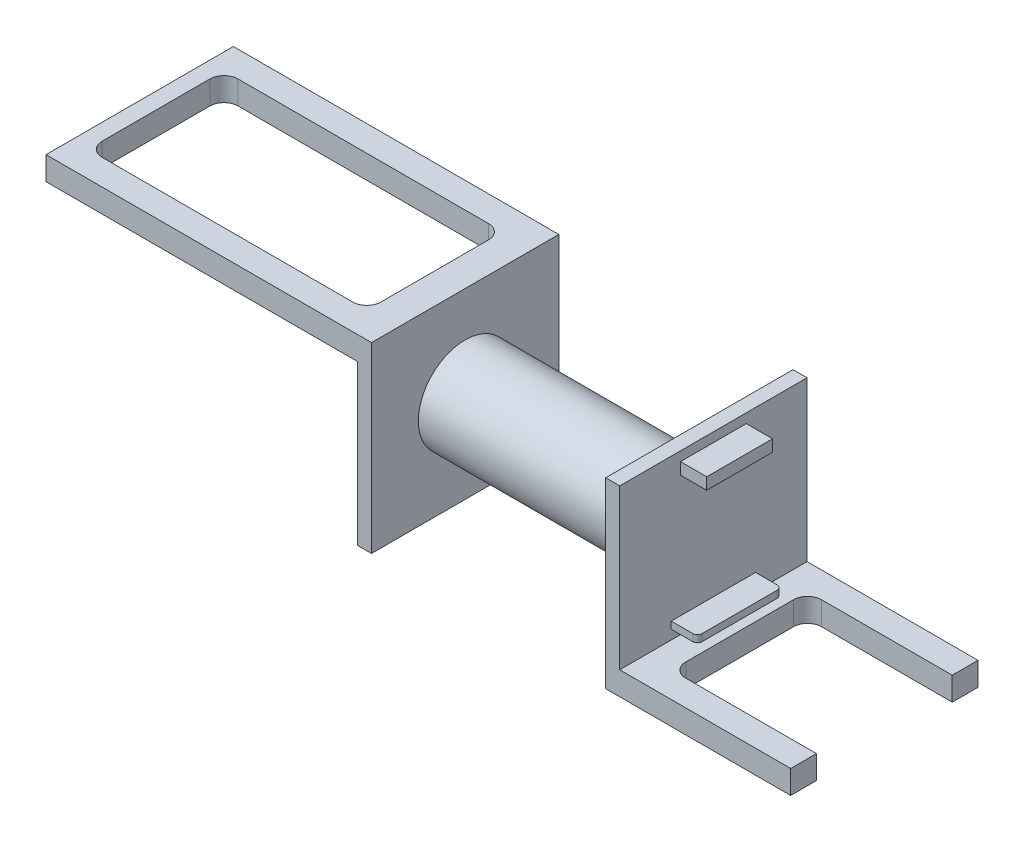
SolidWorks part; units mm, degrees
ref_plane "Front Plane" through (0, 0, 0) normal (0, 0, 1) x (1, 0, 0)
ref_plane "Top Plane" through (0, 0, 0) normal (0, 1, 0) x (1, 0, 0)
ref_plane "Right Plane" through (0, 0, 0) normal (1, 0, 0) x (0, 0, -1)
sketch "Sketch2" plane through (0, 0, 0) normal (0, 1, 0) x (1, 0, 0)
  line L0 (-27.65, 11.5) -> (-27.65, -11.5)
  line L7 (-33.25, -20) -> (33.25, -20)
  line L8 (-33.25, -20) -> (-33.25, 20)
  line L9 (-33.25, 20) -> (33.25, 20)
  line L10 (33.25, -20) -> (33.25, 20)
  line L11 (-24.65, 14.5) -> (28.85, 14.5)
  line L12 (31.85, 11.5) -> (31.85, -11.5)
  line L13 (28.85, -14.5) -> (-24.65, -14.5)
  arc A4 (31.85, -11.5) -> (28.85, -14.5) centre (28.85, -11.5) cw
  arc A5 (28.85, 14.5) -> (31.85, 11.5) centre (28.85, 11.5) cw
  arc A6 (-27.65, 11.5) -> (-24.65, 14.5) centre (-24.65, 11.5) cw
  arc A7 (-27.65, -11.5) -> (-24.65, -14.5) centre (-24.65, -11.5) ccw
  point P0 (0, 0)
  point P7 (0, 0)
  dimension "D1" = 3
extrude "Boss-Extrude1" add sketch "Sketch2" along normal blind 5
sketch "Sketch5" plane through (-33.25, 0, 0) normal (-1, 0, 0) x (0, 0, 1)
  line L1 (20, 0) -> (-20, 0)
  line L2 (20, 0) -> (20, 39)
  line L3 (20, 39) -> (-20, 39)
  line L4 (-20, 0) -> (-20, 39)
  dimension "D1" = 39
extrude "Boss-Extrude3" add sketch "Sketch5" along normal blind 3
sketch "Sketch11" plane through (-33.25, 0, 0) normal (1, 0, 0) x (0, 0, -1)
  line L6 (0, 37) -> (-7.025, 37)
  line L7 (0, 37) -> (7.025, 37)
  line L11 (-7.025, 37) -> (-7.025, 34.5)
  line L12 (-7.025, 34.5) -> (7.025, 34.5)
  line L13 (7.025, 34.5) -> (7.025, 37)
  line L14 (0, 7) -> (-9, 7)
  line L15 (0, 7) -> (9, 7)
  line L16 (9, 7) -> (9, 8.5)
  line L17 (9, 8.5) -> (-9, 8.5)
  line L18 (-9, 8.5) -> (-9, 7)
extrude "Boss-Extrude4" add sketch "Sketch11" along normal blind 5.6
fillet "Fillet4" radius 1 2 edges at (-27.65, 7.75, 9) (-27.65, 7.75, -9)
fillet "Fillet6" radius 10 2 edges at (33.25, 2.5, 20) (33.25, 2.5, -20)
sketch "Sketch12" plane through (0, 0, 0) normal (0, -1, 0) x (1, 0, 0)
  line L0 (23.25, -20) -> (-36.25, -20) construction
  line L1 (33.25, 20) -> (3.25, 20)
  line L2 (33.25, 20) -> (33.25, -20)
  line L3 (33.25, -20) -> (3.25, -20)
  line L4 (3.25, 20) -> (3.25, -20)
extrude "Cut-Extrude1" cut sketch "Sketch12" against normal blind 10
sketch "Sketch13" plane through (-36.25, 0, 0) normal (-1, 0, 0) x (0, 0, 1)
  circle A0 centre (0, 19.5) radius 10
extrude "Boss-Extrude5" add sketch "Sketch13" along normal blind 50
sketch "Sketch14" plane through (-86.25, 0, 0) normal (-1, 0, 0) x (0, 0, 1)
  line L1 (20, 0) -> (-20, 0)
  line L2 (20, 0) -> (20, 39)
  line L3 (20, 39) -> (-20, 39)
  line L4 (-20, 0) -> (-20, 39)
  line L5 (20, 0) -> (-20, 39) construction
  line L6 (20, 39) -> (-20, 0) construction
  point P0 (0, 19.5)
extrude "Boss-Extrude6" add sketch "Sketch14" along normal blind 3
sketch "Sketch15" plane through (-89.25, 0, 0) normal (-1, 0, 0) x (0, 0, 1)
  line L0 (20, 0) -> (20, 39) construction
  line L1 (-20, 39) -> (20, 39)
  line L2 (-20, 39) -> (-20, 34)
  line L3 (-20, 34) -> (20, 34)
  line L4 (20, 39) -> (20, 34)
extrude "Boss-Extrude7" add sketch "Sketch15" along normal blind 66.5
sketch "Sketch16" plane through (0, 34, 0) normal (0, -1, 0) x (1, 0, 0)
  line L2 (-152.25, 11.5) -> (-152.25, -11.5)
  line L3 (-149.25, -14.5) -> (-95.75, -14.5)
  line L4 (-149.25, 14.5) -> (-95.75, 14.5)
  line L5 (-92.75, 11.5) -> (-92.75, -11.5)
  arc A0 (-95.75, -14.5) -> (-92.75, -11.5) centre (-95.75, -11.5) ccw
  arc A1 (-92.75, 11.5) -> (-95.75, 14.5) centre (-95.75, 11.5) ccw
  arc A2 (-152.25, -11.5) -> (-149.25, -14.5) centre (-149.25, -11.5) ccw
  arc A3 (-152.25, 11.5) -> (-149.25, 14.5) centre (-149.25, 11.5) cw
  point P0 (0, 0)
  dimension "D1" = 3
  dimension "D2" = 3
extrude "Cut-Extrude2" cut sketch "Sketch16" against normal blind 5
